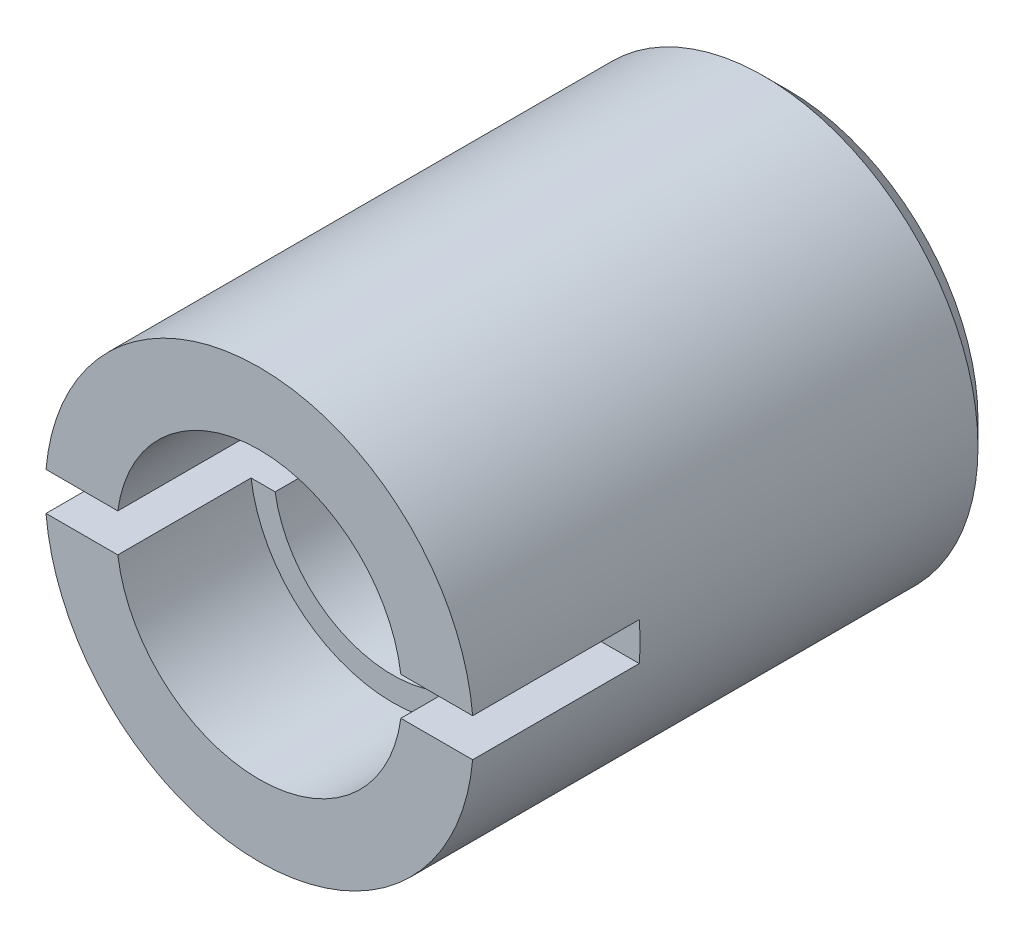
SolidWorks part; units mm, degrees
ref_plane "Front Plane" through (0, 0, 0) normal (1, 0, 0) x (0, 1, 0)
ref_plane "Top Plane" through (0, 0, 0) normal (0, 0, 1) x (0, 1, 0)
ref_plane "Right Plane" through (0, 0, 0) normal (0, 1, 0) x (-1, 0, 0)
sketch "Sketch1" plane through (0, 0, 0) normal (0, 0, 1) x (0, 1, 0)
  circle A0 centre (0, 0) radius 2.75
  circle A1 centre (0, 0) radius 1.4
  dimension "D1" = 5.5
  dimension "D2" = 2.8
extrude "Boss-Extrude1" add sketch "Sketch1" along normal blind 0.5
sketch "Sketch2" plane through (0, 0, 0.5) normal (0, 0, 1) x (1, 0, 0)
  circle A0 centre (0, 0) radius 1.4
  circle A1 centre (0, 0) radius 1.4 construction
  circle A2 centre (0, 0) radius 4.5
  dimension "D1" = 9
extrude "Boss-Extrude2" add sketch "Sketch2" along normal blind 6.1
chamfer "Chamfer1" distance 0.5 angle 45 1 edges at (4.5, 0, 0.5)
sketch "Sketch3" plane through (0, 0, 6.6) normal (0, 0, 1) x (1, 0, 0)
  circle A0 centre (0, 0) radius 2.5
  circle A1 centre (0, 0) radius 4.5
  circle A2 centre (0, 0) radius 4.5 construction
  dimension "D1" = 5
extrude "Boss-Extrude3" add sketch "Sketch3" along normal blind 2.2
sketch "Sketch4" plane through (0, 0, 8.8) normal (0, 0, 1) x (1, 0, 0)
  circle A0 centre (0, 0) radius 4.5
  circle A1 centre (0, 0) radius 4.5 construction
  circle A2 centre (0, 0) radius 3
  dimension "D1" = 6
extrude "Boss-Extrude4" add sketch "Sketch4" along normal blind 2.8
sketch "Sketch5" plane through (0, 0, 0) normal (1, 0, 0) x (0, 1, 0)
  line L0 (3, 11.6) -> (-3, 11.6) construction
  line L1 (-0.4, 11.6) -> (0.4, 11.6)
  line L2 (-0.4, 11.6) -> (-0.4, 8.1)
  line L3 (-0.4, 8.1) -> (0.4, 8.1)
  line L4 (0.4, 11.6) -> (0.4, 8.1)
  point P6 (0, 11.6)
  dimension "D1" = 3.5
  dimension "D2" = 0.8
extrude "Cut-Extrude1" cut sketch "Sketch5" against normal mid plane 9
